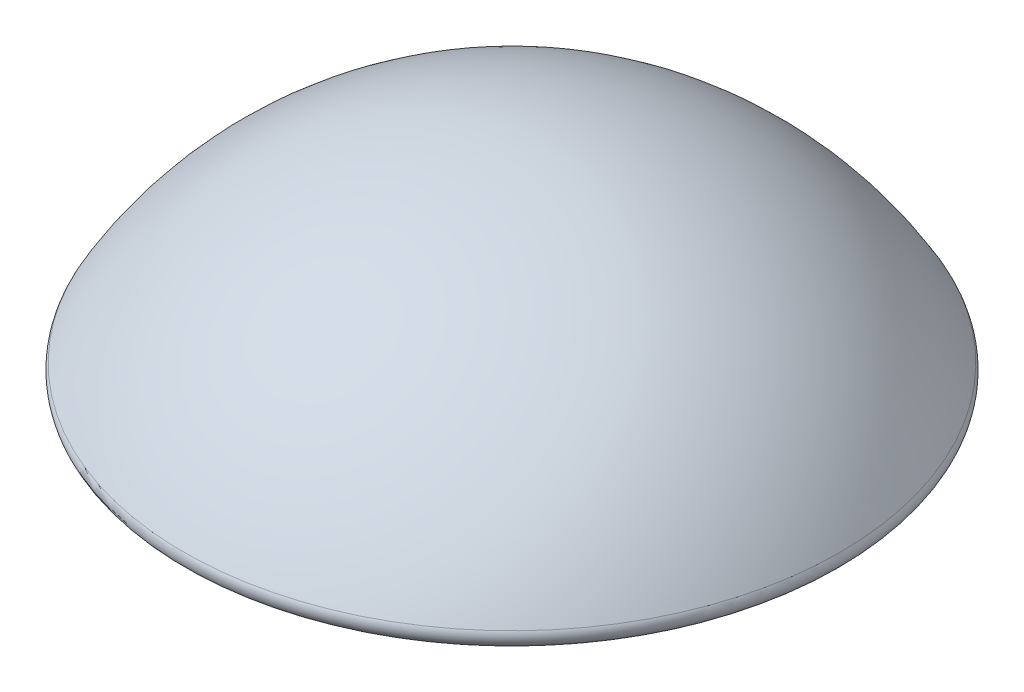
SolidWorks part; units mm, degrees
ref_plane "Front Plane" through (0, 0, 0) normal (0, 0, 1) x (1, 0, 0)
ref_plane "Top Plane" through (0, 0, 0) normal (0, 1, 0) x (1, 0, 0)
ref_plane "Right Plane" through (0, 0, 0) normal (1, 0, 0) x (0, 0, -1)
sketch "Sketch1" plane through (0, 0, 0) normal (0, 0, 1) x (1, 0, 0)
  line L0 (0, 0) -> (0, -95.25)
  line L1 (0, -95.25) -> (0, -101.6)
  line L2 (82.4889, 47.625) -> (0, 0) construction
  line L3 (0, 0) -> (-82.4889, 47.625) construction
  line L4 (0, 101.6) -> (0, 95.25)
  arc A0 (-82.4889, 47.625) -> (82.4889, 47.625) centre (0, 0) cw
  arc A1 (-87.9882, 50.8) -> (87.9882, 50.8) centre (0, 0) cw
  arc A2 (82.4889, 47.625) -> (87.9882, 50.8) centre (85.2386, 49.2125) ccw
  arc A3 (-87.9882, 50.8) -> (-82.4889, 47.625) centre (-85.2386, 49.2125) ccw
  dimension "D1" = 6.35
  dimension "D2" = 101.6
  dimension "D3" = 240
revolve "Revolve1" add sketch "Sketch1" angle 360 about L0
sketch3d "3DSketch1"
  circle A0 centre (0, 47.625, 0) radius 82.4889 construction
  point P2 (0, 130.1139, 0)
